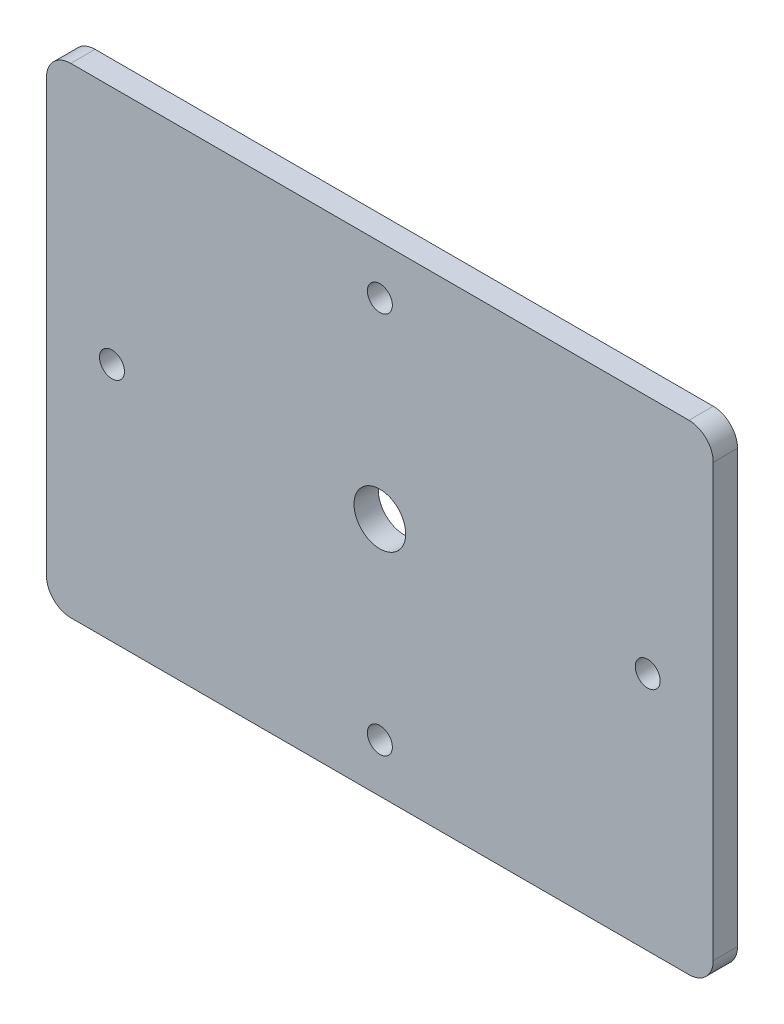
SolidWorks part; units mm, degrees
material "Acrylic (Medium-high impact)"
ref_plane "Front Plane" through (0, 0, 0) normal (0, 0, 1) x (1, 0, 0)
ref_plane "Top Plane" through (0, 0, 0) normal (0, 1, 0) x (1, 0, 0)
ref_plane "Right Plane" through (0, 0, 0) normal (1, 0, 0) x (0, 0, -1)
sketch "Sketch1" plane through (0, 0, 0) normal (0, 0, 1) x (1, 0, 0)
  line L1 (0, 0) -> (87.122, 0)
  line L2 (0, 0) -> (0, 62.738)
  line L3 (0, 62.738) -> (87.122, 62.738)
  line L4 (87.122, 0) -> (87.122, 62.738)
  dimension "D1" = 62.738
  dimension "D2" = 87.122
extrude "Boss-Extrude1" add sketch "Sketch1" along normal blind 3.175
hole_wizard "#4 Clearance Hole1" positions "Sketch2" profile "Sketch3" hole size "#4" standard "ANSI Inch" end condition through all
sketch "Sketch2" plane through (0, 0, 3.175) normal (0, 0, 1) x (1, 0, 0)
  line L0 (0, 62.738) -> (87.122, 0) construction
  line L2 (43.561, 31.369) -> (78.561, 31.369) construction
  line L3 (43.561, 31.369) -> (8.561, 31.369) construction
  line L4 (43.561, 31.369) -> (43.561, 56.369) construction
  line L5 (43.561, 31.369) -> (43.561, 6.369) construction
  point P9 (78.561, 31.369)
  point P12 (8.561, 31.369)
  point P14 (43.561, 56.369)
  point P17 (43.561, 6.369)
  dimension "D1" = 70
  dimension "D2" = 50
sketch "Sketch3" plane through (43.561, 6.369, 3.175) normal (1, 0, 0) x (0, -1, 0)
  line L0 (0, 0) -> (0, 3.175)
  line L1 (0, 3.175) -> (1.6319, 3.175)
  line L2 (1.6319, 3.175) -> (1.6319, 0)
  line L5 (1.6319, 0) -> (0, 0)
  line L11 (0, -6.35) -> (0, 107.95) construction
  dimension "Thru Hole Dia." = 3.2639
  dimension "Thru Hole Depth" = 3.175
hole_wizard "1/4 Clearance Hole1" positions "Sketch7" profile "Sketch8" hole size "1/4" standard "ANSI Inch" end condition through all
sketch "Sketch7" plane through (0, 0, 3.175) normal (0, 0, 1) x (1, 0, 0)
  line L0 (0, 62.738) -> (87.122, 0) construction
  point P6 (43.561, 31.369)
sketch "Sketch8" plane through (43.561, 31.369, 3.175) normal (1, 0, 0) x (0, -1, 0)
  line L0 (0, 0) -> (0, 3.175)
  line L1 (0, 3.175) -> (3.3782, 3.175)
  line L2 (3.3782, 3.175) -> (3.3782, 0)
  line L5 (3.3782, 0) -> (0, 0)
  line L11 (0, -6.35) -> (0, 107.95) construction
  dimension "Thru Hole Dia." = 6.7564
  dimension "Thru Hole Depth" = 3.175
fillet "Fillet1" radius 3.175 4 edges at (0, 62.738, 1.5875) (0, 0, 1.5875) (87.122, 0, 1.5875) (87.122, 62.738, 1.5875)
